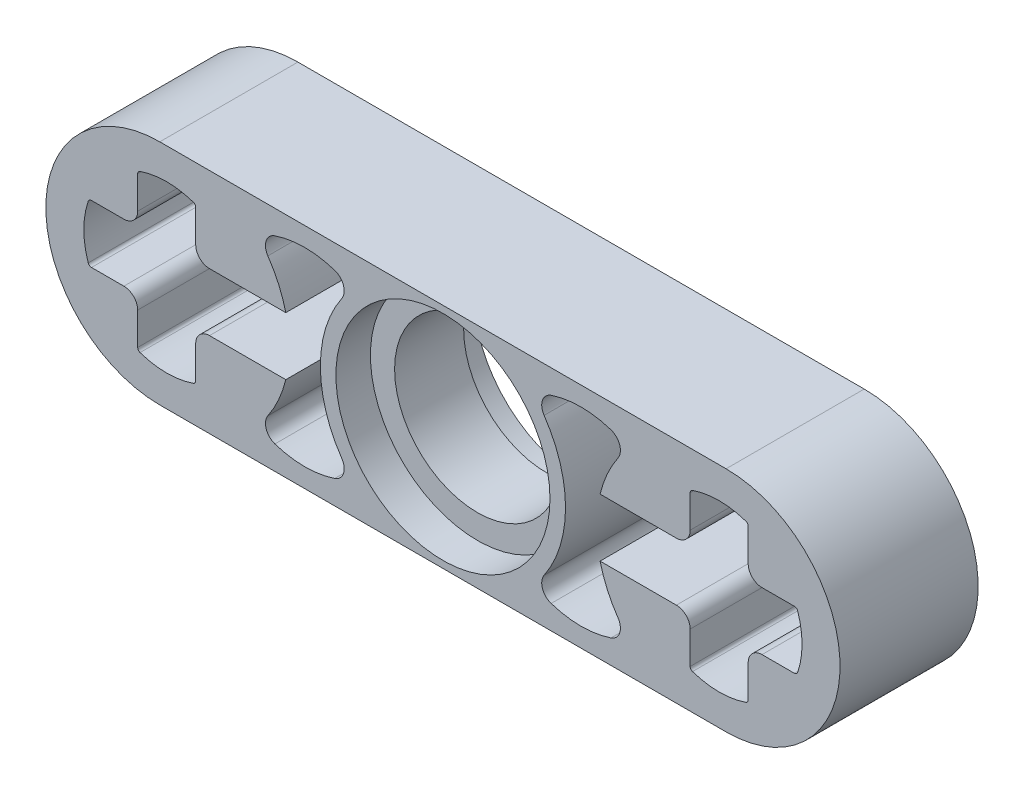
SolidWorks part; units mm, degrees
ref_plane "Front Plane" through (0, 0, 0) normal (0, 0, 1) x (1, 0, 0)
ref_plane "Top Plane" through (0, 0, 0) normal (0, 1, 0) x (1, 0, 0)
ref_plane "Right Plane" through (0, 0, 0) normal (1, 0, 0) x (0, 0, -1)
sketch "Sketch2" plane through (0, 0, 0) normal (0, 0, 1) x (1, 0, 0)
  line L1 (-9.24, 0.84) -> (-10.1777, 0.84)
  line L2 (-8.84, -2.1777) -> (-8.84, -1.24)
  line L3 (-7.16, -2.1777) -> (-7.16, -1.24)
  line L4 (-5.8223, 0.84) -> (-6.76, 0.84)
  line L5 (-5.8223, -0.84) -> (-6.76, -0.84)
  line L6 (-8.84, 1.24) -> (-8.84, 2.1777)
  line L7 (-7.16, 1.24) -> (-7.16, 2.1777)
  line L8 (-9.24, -0.84) -> (-10.1777, -0.84)
  line L9 (-5.7518, 0.84) -> (-4.5508, 0.84)
  line L10 (-5.7518, -0.84) -> (-4.5508, -0.84)
  line L11 (-5.8223, -0.84) -> (-5.7518, -0.84)
  line L12 (-5.8223, 0.84) -> (-5.7518, 0.84)
  line L13 (0, -3.63) -> (0, 3.63) construction
  line L14 (8.84, 1.24) -> (8.84, 2.1777)
  line L15 (7.16, 1.24) -> (7.16, 2.1777)
  line L16 (5.8223, 0.84) -> (6.76, 0.84)
  line L17 (5.8223, 0.84) -> (5.7518, 0.84)
  line L18 (5.7518, 0.84) -> (4.5508, 0.84)
  line L19 (5.7518, -0.84) -> (4.5508, -0.84)
  line L20 (5.8223, -0.84) -> (5.7518, -0.84)
  line L21 (5.8223, -0.84) -> (6.76, -0.84)
  line L22 (7.16, -2.1777) -> (7.16, -1.24)
  line L23 (8.84, -2.1777) -> (8.84, -1.24)
  line L24 (9.24, -0.84) -> (10.1777, -0.84)
  line L25 (9.24, 0.84) -> (10.1777, 0.84)
  line L27 (-8.2, 3.3) -> (8.2, 3.3)
  line L28 (-8.2, -3.3) -> (8.2, -3.3)
  circle A0 centre (0, 0) radius 2.4
  arc A1 (-4.866, -2.6101) -> (-3.134, -2.6101) centre (-4, 0) ccw
  arc A2 (-2.9299, -2.0046) -> (-3.134, -2.6101) centre (-3.26, -2.2304) cw
  arc A3 (-2.9299, -2.0046) -> (-2.9299, 2.0046) centre (0, 0) cw
  arc A4 (-2.9299, 2.0046) -> (-3.134, 2.6101) centre (-3.26, 2.2304) ccw
  arc A5 (-3.134, 2.6101) -> (-4.866, 2.6101) centre (-4, 0) ccw
  arc A6 (-5.0701, 2.0046) -> (-4.866, 2.6101) centre (-4.74, 2.2304) cw
  arc A7 (-5.0701, -2.0046) -> (-5.0701, 2.0046) centre (-8, 0) ccw
  arc A8 (-5.0701, -2.0046) -> (-4.866, -2.6101) centre (-4.74, -2.2304) ccw
  arc A9 (-7.2278, 2.2724) -> (-8.7722, 2.2724) centre (-8, 0) ccw
  arc A10 (-10.2724, 0.7722) -> (-10.2724, -0.7722) centre (-8, 0) ccw
  arc A11 (-8.7722, -2.2724) -> (-7.2278, -2.2724) centre (-8, 0) ccw
  arc A12 (-8.84, -1.24) -> (-9.24, -0.84) centre (-9.24, -1.24) ccw
  arc A13 (-7.16, -1.24) -> (-6.76, -0.84) centre (-6.76, -1.24) cw
  arc A14 (-6.76, 0.84) -> (-7.16, 1.24) centre (-6.76, 1.24) cw
  arc A15 (-9.24, 0.84) -> (-8.84, 1.24) centre (-9.24, 1.24) ccw
  arc A16 (-10.1777, 0.84) -> (-10.2724, 0.7722) centre (-10.1777, 0.74) ccw
  arc A17 (-10.1777, -0.84) -> (-10.2724, -0.7722) centre (-10.1777, -0.74) cw
  arc A18 (-8.7722, -2.2724) -> (-8.84, -2.1777) centre (-8.74, -2.1777) cw
  arc A19 (-7.2278, -2.2724) -> (-7.16, -2.1777) centre (-7.26, -2.1777) ccw
  arc A20 (-7.2278, 2.2724) -> (-7.16, 2.1777) centre (-7.26, 2.1777) cw
  arc A21 (-8.84, 2.1777) -> (-8.7722, 2.2724) centre (-8.74, 2.1777) cw
  arc A22 (-4.5508, -0.84) -> (-4.5508, 0.84) centre (-8, 0) ccw
  arc A31 (5.0701, -2.0046) -> (4.866, -2.6101) centre (4.74, -2.2304) cw
  arc A32 (5.0701, -2.0046) -> (5.0701, 2.0046) centre (8, 0) cw
  arc A33 (5.0701, 2.0046) -> (4.866, 2.6101) centre (4.74, 2.2304) ccw
  arc A34 (3.134, 2.6101) -> (4.866, 2.6101) centre (4, 0) cw
  arc A35 (2.9299, 2.0046) -> (3.134, 2.6101) centre (3.26, 2.2304) cw
  arc A36 (2.9299, -2.0046) -> (2.9299, 2.0046) centre (0, 0) ccw
  arc A37 (2.9299, -2.0046) -> (3.134, -2.6101) centre (3.26, -2.2304) ccw
  arc A38 (4.866, -2.6101) -> (3.134, -2.6101) centre (4, 0) cw
  arc A39 (9.24, 0.84) -> (8.84, 1.24) centre (9.24, 1.24) cw
  arc A40 (8.84, 2.1777) -> (8.7722, 2.2724) centre (8.74, 2.1777) ccw
  arc A41 (7.2278, 2.2724) -> (8.7722, 2.2724) centre (8, 0) cw
  arc A42 (7.2278, 2.2724) -> (7.16, 2.1777) centre (7.26, 2.1777) ccw
  arc A43 (6.76, 0.84) -> (7.16, 1.24) centre (6.76, 1.24) ccw
  arc A44 (4.5508, -0.84) -> (4.5508, 0.84) centre (8, 0) cw
  arc A45 (7.16, -1.24) -> (6.76, -0.84) centre (6.76, -1.24) ccw
  arc A46 (7.2278, -2.2724) -> (7.16, -2.1777) centre (7.26, -2.1777) cw
  arc A47 (8.7722, -2.2724) -> (7.2278, -2.2724) centre (8, 0) cw
  arc A48 (8.7722, -2.2724) -> (8.84, -2.1777) centre (8.74, -2.1777) ccw
  arc A49 (8.84, -1.24) -> (9.24, -0.84) centre (9.24, -1.24) cw
  arc A50 (10.1777, -0.84) -> (10.2724, -0.7722) centre (10.1777, -0.74) ccw
  arc A51 (10.2724, 0.7722) -> (10.2724, -0.7722) centre (8, 0) cw
  arc A52 (10.1777, 0.84) -> (10.2724, 0.7722) centre (10.1777, 0.74) cw
  arc A56 (-8.2, 3.3) -> (-8.2, -3.3) centre (-8.2, 0) ccw
  arc A57 (8.2, 3.3) -> (8.2, -3.3) centre (8.2, 0) cw
  point P115 (0, 3.3)
  point P118 (0, -3.3)
  dimension "D1" = 4.8
  dimension "D2" = 4
  dimension "D3" = 8
extrude "Boss-Extrude1" add sketch "Sketch2" along normal mid plane 4 contours A57 L27 A56 L28 A0 L6 A21 A9 A20 L7 A14 L4 L12 L9 A7 A6 A5 A4 A3 A2 A1 A8 L10 L11 L5 A13 L3 A19 A11 A18 L2 A12 L8 A17 A10 A16 L1 A15 L25 A52 A51 A50 L24 A49 L23 A48 A47
sketch "Sketch4" plane through (0, 0, 2) normal (0, 0, 1) x (1, 0, 0)
  circle A0 centre (0, 0) radius 3.1
  dimension "D1" = 6.2
extrude "Cut-Extrude1" cut sketch "Sketch4" against normal blind 1 contours A0
mirror "Mirror1" about plane through (0, 0, 0) normal (0, 0, 1) of "Cut-Extrude1"
